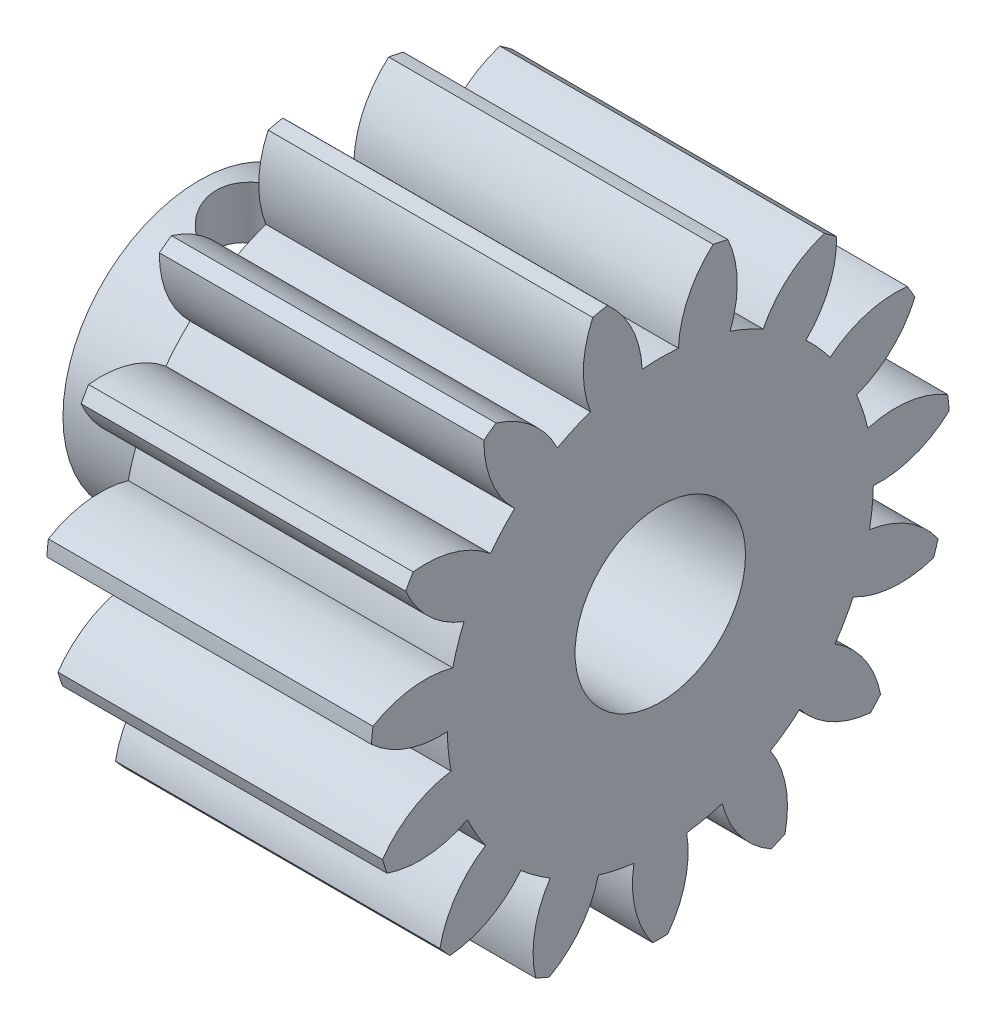
SolidWorks part; units mm, degrees
ref_plane "Plane1" through (0, 0, 0) normal (0, 0, 1) x (1, 0, 0)
ref_plane "Plane2" through (0, 0, 0) normal (0, 1, 0) x (1, 0, 0)
ref_plane "Plane3" through (0, 0, 0) normal (1, 0, 0) x (0, 0, -1)
sketch "HoldingSke" plane through (0, 0, 0) normal (0, 1, 0) x (1, 0, 0)
  line L0 (0, 0) -> (0.9659, -0.2588)
  line L1 (-15, 0) -> (100, 0) construction
  line L2 (0, 0) -> (-2.1039, 2.3779)
  line L3 (0, 0) -> (-11.863, 4.5341)
  line L4 (0, 0) -> (8.3417, 2.2352)
  line L5 (0, 0) -> (-46.8476, -17.4728)
  line L6 (0, 0) -> (-10.5278, -7.1032)
  line L7 (-2.1039, 2.3779) -> (8.6586, 51.2059)
  line L8 (-76.2, 54.61) -> (-76.1, 54.61)
  line L9 (-71.009, 38.7566) -> (-53.1078, 45.2721)
  line L10 (-76.2, 71.12) -> (104.1128, 71.12)
  line L11 (0, 0) -> (-12.7, 0)
  line L12 (-76.2, 101.6) -> (-76.162, 101.6)
  line L13 (24.9733, 27.94) -> (52.9518, 28.4284)
  line L14 (24.9733, 27.94) -> (24.9743, 27.94)
  line L15 (24.9733, 27.94) -> (100.4006, 29.5858)
  line L16 (-63.627, -1) -> (-12.827, -1)
  circle A0 centre (0, 0) radius 0.4
  circle A1 centre (0, 0) radius 6.249
  circle A2 centre (0, 0) radius 37.5
  circle A3 centre (0, 0) radius 0.4
  dimension "MHD" = 12.498
  dimension "Hub_dia" = 75
  dimension "Bore" = 0.8
  dimension "MBD" = 0.8
  dimension "Num_teeth" = 15
  dimension "Pitch" = 1
  dimension "Overall_len" = 50
  dimension "Show_teeth" = 15
  dimension "Thickness" = 12.7
  dimension "OAL" = 50.0001
  dimension "T_dim" = 0.1
  dimension "Ap" = 20
  dimension "H" = 19.05
  dimension "Pitch_radius" = 180.3128
  dimension "Width" = 12.7
  dimension "Backlash" = 0.038
  dimension "Addendum_fac" = 1
  dimension "Dedendum_fac" = 1.25
  dimension "Clearance_fac" = 0.25
  dimension "Dedendum_add" = 0.001
  dimension "Module" = 1
sketch "BasProSke" plane through (0, 0, 0) normal (0, 1, 0) x (1, 0, 0)
  line L0 (-10, 0) -> (60, 0) construction
  line L1 (0, 0) -> (0, 8.5)
  line L2 (0, 0) -> (12.7, 0)
  line L3 (12.7, 0) -> (12.7, 8.5)
  line L4 (12.7, 8.5) -> (0, 8.5)
  dimension "Thickness" = 12.7
  dimension "Diameter" = 17
revolve "Base-Revolve" add sketch "BasProSke" angle 360 about L0
sketch "TooCutSke" plane through (0, 0, 0) normal (1, 0, 0) x (0, 0, -1)
  line L1 (0, 0) -> (0, 107) construction
  line L2 (0, 0) -> (-0.8504, 7.4516) construction
  line L3 (0, 0) -> (-3.1044, 14.6049) construction
  line L4 (-0.8504, 7.4516) -> (-1.5522, 7.3025) construction
  arc A0 (0.5316, 6.2263) -> (-0.5316, 6.2263) centre (0, 0) ccw
  arc A1 (1.5766, 8.3784) -> (-1.5766, 8.3784) centre (0, 0) ccw
  circle A2 centre (0, 0) radius 7.5 construction
  circle A3 centre (0, 0) radius 7.0477 construction
  arc A4 (-0.5316, 6.2263) -> (-1.5766, 8.3784) centre (-3.5289, 6.1005) ccw
  arc A5 (1.5766, 8.3784) -> (0.5316, 6.2263) centre (3.5289, 6.1005) ccw
  dimension "Root_dia" = 12.498
  dimension "Overcut_dia" = 17.0508
  dimension "Pitch_dia" = 15
  dimension "Base_dia" = 14.0954
  dimension "Flank_rad" = 3
  dimension "Half_ang" = 12
  dimension "Half_CT" = 0.7175
extrude "ToothCut" cut sketch "TooCutSke" along normal through all
fillet "Breaks" [suppressed] radius 0.02
fillet "RootFillets" [suppressed] radius 0.251
pattern_circular "TeethCuts" count 15 every 24 about axis through (-10, 0, 0) along (1, 0, 0) of "ToothCut", "RootFillets", "Breaks"
sketch "HubNeaOneSke" plane through (0, 0, 0) normal (-1, 0, 0) x (0, 0, 1)
  circle A0 centre (0, 0) radius 6.249
  dimension "Diameter" = 12.498
extrude "HubNearOne" [suppressed] add sketch "HubNeaOneSke" along normal blind 37.3001
sketch "HubNeaBotSke" plane through (0, 0, 0) normal (-1, 0, 0) x (0, 0, 1)
  circle A0 centre (0, 0) radius 6.249
  dimension "Diameter" = 12.498
extrude "HubNearBoth" [suppressed] add sketch "HubNeaBotSke" along normal blind 18.65
ref_plane "FarPln" through (12.7, 0, 0) normal (1, 0, 0) x (0, 0, -1)
sketch "HubFarSke" plane through (12.7, 0, 0) normal (1, 0, 0) x (0, 0, -1)
  circle A0 centre (0, 0) radius 6.249
  dimension "Diameter" = 12.498
extrude "HubFar" [suppressed] add sketch "HubFarSke" along normal blind 18.65
sketch "BorSke" plane through (0, 0, 0) normal (1, 0, 0) x (0, 0, -1)
  circle A0 centre (0, 0) radius 0.4
  dimension "Diameter" = 0.8
extrude "Bore" cut sketch "BorSke" along normal mid plane 100.0001
sketch "KeySke" plane through (0, 0, 0) normal (1, 0, 0) x (0, 0, -1)
  line L0 (-0.05, 0) -> (-0.05, 0.5)
  line L1 (-0.05, 0.5) -> (0.05, 0.5)
  line L2 (0.05, 0.5) -> (0.05, 0)
  line L3 (0, 0) -> (0, 34) construction
  line L4 (-0.05, 0) -> (0.05, 0)
  dimension "Offset" = 0.5
  dimension "Width" = 0.1
extrude "Keyway" [suppressed] cut sketch "KeySke" along normal mid plane 100.0001
pattern_circular "Keyway2" [suppressed] count 2 every 90 about axis through (-10, 0, 0) along (1, 0, 0)
sketch "Croquis2" plane through (12.7, 0, 0) normal (1, 0, 0) x (0, 0, -1)
  arc A60 (-8.4736, 0.67) -> (-6.2478, -0.1222) centre (-6.436, 2.8719) ccw
  arc A61 (-6.2478, -0.1222) -> (-6.1367, -1.1795) centre (0, 0) ccw
  arc A62 (-6.1367, -1.1795) -> (-8.1491, -2.4171) centre (-5.6982, -4.1473) ccw
  arc A63 (-8.1491, -2.4171) -> (-8.0135, -2.8344) centre (0, 0) ccw
  arc A64 (-8.0135, -2.8344) -> (-5.658, -2.6528) centre (-7.0477, 0.0059) ccw
  arc A65 (-5.658, -2.6528) -> (-5.1264, -3.5735) centre (0, 0) ccw
  arc A66 (-5.1264, -3.5735) -> (-6.4614, -5.5227) centre (-3.5188, -6.1064) ccw
  arc A67 (-6.4614, -5.5227) -> (-6.1678, -5.8487) centre (0, 0) ccw
  arc A68 (-6.1678, -5.8487) -> (-4.0898, -4.7248) centre (-6.4408, -2.8612) ccw
  arc A69 (-4.0898, -4.7248) -> (-3.2297, -5.3497) centre (0, 0) ccw
  arc A70 (-3.2297, -5.3497) -> (-3.6565, -7.6733) centre (-0.7308, -7.0097) ccw
  arc A71 (-3.6565, -7.6733) -> (-3.2557, -7.8518) centre (0, 0) ccw
  arc A72 (-3.2557, -7.8518) -> (-1.8145, -5.9798) centre (-4.7202, -5.2335) ccw
  arc A73 (-1.8145, -5.9798) -> (-0.7746, -6.2008) centre (0, 0) ccw
  arc A74 (-0.7746, -6.2008) -> (-0.2194, -8.4972) centre (2.1834, -6.7009) ccw
  arc A75 (-0.2194, -8.4972) -> (0.2194, -8.4972) centre (0, 0) ccw
  arc A76 (0.2194, -8.4972) -> (0.7746, -6.2008) centre (-2.1834, -6.7009) ccw
  arc A77 (0.7746, -6.2008) -> (1.8145, -5.9798) centre (0, 0) ccw
  arc A78 (1.8145, -5.9798) -> (3.2557, -7.8518) centre (4.7202, -5.2335) ccw
  arc A79 (3.2557, -7.8518) -> (3.6565, -7.6733) centre (0, 0) ccw
  arc A80 (3.6565, -7.6733) -> (3.2297, -5.3497) centre (0.7308, -7.0097) ccw
  arc A81 (3.2297, -5.3497) -> (4.0898, -4.7248) centre (0, 0) ccw
  arc A82 (4.0898, -4.7248) -> (6.1678, -5.8487) centre (6.4408, -2.8612) ccw
  arc A83 (6.1678, -5.8487) -> (6.4614, -5.5227) centre (0, 0) ccw
  arc A84 (6.4614, -5.5227) -> (5.1264, -3.5735) centre (3.5188, -6.1064) ccw
  arc A85 (5.1264, -3.5735) -> (5.658, -2.6528) centre (0, 0) ccw
  arc A86 (5.658, -2.6528) -> (8.0135, -2.8344) centre (7.0477, 0.0059) ccw
  arc A87 (8.0135, -2.8344) -> (8.1491, -2.4171) centre (0, 0) ccw
  arc A88 (8.1491, -2.4171) -> (6.1367, -1.1795) centre (5.6982, -4.1473) ccw
  arc A89 (6.1367, -1.1795) -> (6.2478, -0.1222) centre (0, 0) ccw
  arc A90 (6.2478, -0.1222) -> (8.4736, 0.67) centre (6.436, 2.8719) ccw
  arc A91 (8.4736, 0.67) -> (8.4277, 1.1064) centre (0, 0) ccw
  arc A92 (8.4277, 1.1064) -> (6.0859, 1.4185) centre (6.8925, -1.471) ccw
  arc A93 (6.0859, 1.4185) -> (5.7573, 2.4296) centre (0, 0) ccw
  arc A94 (5.7573, 2.4296) -> (7.4685, 4.0586) centre (4.7115, 5.2414) ccw
  arc A95 (7.4685, 4.0586) -> (7.2491, 4.4386) centre (0, 0) ccw
  arc A96 (7.2491, 4.4386) -> (4.9828, 3.7712) centre (6.8949, 1.4595) ccw
  arc A97 (4.9828, 3.7712) -> (4.2714, 4.5613) centre (0, 0) ccw
  arc A98 (4.2714, 4.5613) -> (5.172, 6.7454) centre (2.1723, 6.7046) ccw
  arc A99 (5.172, 6.7454) -> (4.817, 7.0033) centre (0, 0) ccw
  arc A100 (4.817, 7.0033) -> (3.0181, 5.4718) centre (5.7052, 4.1378) ccw
  arc A101 (3.0181, 5.4718) -> (2.0469, 5.9043) centre (0, 0) ccw
  arc A102 (2.0469, 5.9043) -> (1.9812, 8.2659) centre (-0.7425, 7.0085) ccw
  arc A103 (1.9812, 8.2659) -> (1.5521, 8.3571) centre (0, 0) ccw
  arc A104 (1.5521, 8.3571) -> (0.5316, 6.2263) centre (3.5289, 6.1005) ccw
  arc A105 (0.5316, 6.2263) -> (-0.5316, 6.2263) centre (0, 0) ccw
  arc A106 (-0.5316, 6.2263) -> (-1.5521, 8.3571) centre (-3.5289, 6.1005) ccw
  arc A107 (-1.5521, 8.3571) -> (-1.9812, 8.2659) centre (0, 0) ccw
  arc A108 (-1.9812, 8.2659) -> (-2.0469, 5.9043) centre (0.7425, 7.0085) ccw
  arc A109 (-2.0469, 5.9043) -> (-3.0181, 5.4718) centre (0, 0) ccw
  arc A110 (-3.0181, 5.4718) -> (-4.817, 7.0033) centre (-5.7052, 4.1378) ccw
  arc A111 (-4.817, 7.0033) -> (-5.172, 6.7454) centre (0, 0) ccw
  arc A112 (-5.172, 6.7454) -> (-4.2714, 4.5613) centre (-2.1723, 6.7046) ccw
  arc A113 (-4.2714, 4.5613) -> (-4.9828, 3.7712) centre (0, 0) ccw
  arc A114 (-4.9828, 3.7712) -> (-7.2491, 4.4386) centre (-6.8949, 1.4595) ccw
  arc A115 (-7.2491, 4.4386) -> (-7.4685, 4.0586) centre (0, 0) ccw
  arc A116 (-7.4685, 4.0586) -> (-5.7573, 2.4296) centre (-4.7115, 5.2414) ccw
  arc A117 (-5.7573, 2.4296) -> (-6.0859, 1.4185) centre (0, 0) ccw
  arc A118 (-6.0859, 1.4185) -> (-8.4277, 1.1064) centre (-6.8925, -1.471) ccw
  arc A119 (-8.4277, 1.1064) -> (-8.4736, 0.67) centre (0, 0) ccw
  arc A120 (-8.4736, 0.67) -> (-6.2478, -0.1222) centre (-6.436, 2.8719) ccw
  arc A121 (-6.2478, -0.1222) -> (-6.1367, -1.1795) centre (0, 0) ccw
  arc A122 (-6.1367, -1.1795) -> (-8.1491, -2.4171) centre (-5.6982, -4.1473) ccw
  arc A123 (-8.1491, -2.4171) -> (-8.0135, -2.8344) centre (0, 0) ccw
  arc A124 (-8.0135, -2.8344) -> (-5.658, -2.6528) centre (-7.0477, 0.0059) ccw
  arc A125 (-5.658, -2.6528) -> (-5.1264, -3.5735) centre (0, 0) ccw
  arc A126 (-5.1264, -3.5735) -> (-6.4614, -5.5227) centre (-3.5188, -6.1064) ccw
  arc A127 (-6.4614, -5.5227) -> (-6.1678, -5.8487) centre (0, 0) ccw
  arc A128 (-6.1678, -5.8487) -> (-4.0898, -4.7248) centre (-6.4408, -2.8612) ccw
  arc A129 (-4.0898, -4.7248) -> (-3.2297, -5.3497) centre (0, 0) ccw
  arc A130 (-3.2297, -5.3497) -> (-3.6565, -7.6733) centre (-0.7308, -7.0097) ccw
  arc A131 (-3.6565, -7.6733) -> (-3.2557, -7.8518) centre (0, 0) ccw
  arc A132 (-3.2557, -7.8518) -> (-1.8145, -5.9798) centre (-4.7202, -5.2335) ccw
  arc A133 (-1.8145, -5.9798) -> (-0.7746, -6.2008) centre (0, 0) ccw
  arc A134 (-0.7746, -6.2008) -> (-0.2194, -8.4972) centre (2.1834, -6.7009) ccw
  arc A135 (-0.2194, -8.4972) -> (0.2194, -8.4972) centre (0, 0) ccw
  arc A136 (0.2194, -8.4972) -> (0.7746, -6.2008) centre (-2.1834, -6.7009) ccw
  arc A137 (0.7746, -6.2008) -> (1.8145, -5.9798) centre (0, 0) ccw
  arc A138 (1.8145, -5.9798) -> (3.2557, -7.8518) centre (4.7202, -5.2335) ccw
  arc A139 (3.2557, -7.8518) -> (3.6565, -7.6733) centre (0, 0) ccw
  arc A140 (3.6565, -7.6733) -> (3.2297, -5.3497) centre (0.7308, -7.0097) ccw
  arc A141 (3.2297, -5.3497) -> (4.0898, -4.7248) centre (0, 0) ccw
  arc A142 (4.0898, -4.7248) -> (6.1678, -5.8487) centre (6.4408, -2.8612) ccw
  arc A143 (6.1678, -5.8487) -> (6.4614, -5.5227) centre (0, 0) ccw
  arc A144 (6.4614, -5.5227) -> (5.1264, -3.5735) centre (3.5188, -6.1064) ccw
  arc A145 (5.1264, -3.5735) -> (5.658, -2.6528) centre (0, 0) ccw
  arc A146 (5.658, -2.6528) -> (8.0135, -2.8344) centre (7.0477, 0.0059) ccw
  arc A147 (8.0135, -2.8344) -> (8.1491, -2.4171) centre (0, 0) ccw
  arc A148 (8.1491, -2.4171) -> (6.1367, -1.1795) centre (5.6982, -4.1473) ccw
  arc A149 (6.1367, -1.1795) -> (6.2478, -0.1222) centre (0, 0) ccw
  arc A150 (6.2478, -0.1222) -> (8.4736, 0.67) centre (6.436, 2.8719) ccw
  arc A151 (8.4736, 0.67) -> (8.4277, 1.1064) centre (0, 0) ccw
  arc A152 (8.4277, 1.1064) -> (6.0859, 1.4185) centre (6.8925, -1.471) ccw
  arc A153 (6.0859, 1.4185) -> (5.7573, 2.4296) centre (0, 0) ccw
  arc A154 (5.7573, 2.4296) -> (7.4685, 4.0586) centre (4.7115, 5.2414) ccw
  arc A155 (7.4685, 4.0586) -> (7.2491, 4.4386) centre (0, 0) ccw
  arc A156 (7.2491, 4.4386) -> (4.9828, 3.7712) centre (6.8949, 1.4595) ccw
  arc A157 (4.9828, 3.7712) -> (4.2714, 4.5613) centre (0, 0) ccw
  arc A158 (4.2714, 4.5613) -> (5.172, 6.7454) centre (2.1723, 6.7046) ccw
  arc A159 (5.172, 6.7454) -> (4.817, 7.0033) centre (0, 0) ccw
  arc A160 (4.817, 7.0033) -> (3.0181, 5.4718) centre (5.7052, 4.1378) ccw
  arc A161 (3.0181, 5.4718) -> (2.0469, 5.9043) centre (0, 0) ccw
  arc A162 (2.0469, 5.9043) -> (1.9812, 8.2659) centre (-0.7425, 7.0085) ccw
  arc A163 (1.9812, 8.2659) -> (1.5521, 8.3571) centre (0, 0) ccw
  arc A164 (1.5521, 8.3571) -> (0.5316, 6.2263) centre (3.5289, 6.1005) ccw
  arc A165 (0.5316, 6.2263) -> (-0.5316, 6.2263) centre (0, 0) ccw
  arc A166 (-0.5316, 6.2263) -> (-1.5521, 8.3571) centre (-3.5289, 6.1005) ccw
  arc A167 (-1.5521, 8.3571) -> (-1.9812, 8.2659) centre (0, 0) ccw
  arc A168 (-1.9812, 8.2659) -> (-2.0469, 5.9043) centre (0.7425, 7.0085) ccw
  arc A169 (-2.0469, 5.9043) -> (-3.0181, 5.4718) centre (0, 0) ccw
  arc A170 (-3.0181, 5.4718) -> (-4.817, 7.0033) centre (-5.7052, 4.1378) ccw
  arc A171 (-4.817, 7.0033) -> (-5.172, 6.7454) centre (0, 0) ccw
  arc A172 (-5.172, 6.7454) -> (-4.2714, 4.5613) centre (-2.1723, 6.7046) ccw
  arc A173 (-4.2714, 4.5613) -> (-4.9828, 3.7712) centre (0, 0) ccw
  arc A174 (-4.9828, 3.7712) -> (-7.2491, 4.4386) centre (-6.8949, 1.4595) ccw
  arc A175 (-7.2491, 4.4386) -> (-7.4685, 4.0586) centre (0, 0) ccw
  arc A176 (-7.4685, 4.0586) -> (-5.7573, 2.4296) centre (-4.7115, 5.2414) ccw
  arc A177 (-5.7573, 2.4296) -> (-6.0859, 1.4185) centre (0, 0) ccw
  arc A178 (-6.0859, 1.4185) -> (-8.4277, 1.1064) centre (-6.8925, -1.471) ccw
  arc A179 (-8.4277, 1.1064) -> (-8.4736, 0.67) centre (0, 0) ccw
  dimension "D1" = 0
extrude "Cortar-Extruir1" cut sketch "Croquis2" against normal blind 3.18
ref_plane "Plano2" through (4.76, 0, 0) normal (1, 0, 0) x (0, 0, -1)
sketch "Croquis3" plane through (4.76, 0, 0) normal (1, 0, 0) x (0, 0, -1)
  circle A0 centre (0, 0) radius 7.5
  dimension "D1" = 15
sketch "Croquis4" plane through (9.52, 0, 0) normal (1, 0, 0) x (0, 0, -1)
  circle A0 centre (0, 0) radius 2.5
  dimension "D1" = 5
extrude "Cortar-Extruir2" cut sketch "Croquis4" against normal up to surface (9.52 mm away) up to face at (0, 0, -0.4)
sketch "Croquis5" plane through (0, 0, 0) normal (-1, 0, 0) x (0, 0, 1)
  circle A0 centre (0, 0) radius 4
  circle A1 centre (0, 0) radius 2.5 construction
  circle A2 centre (0, 0) radius 2.5
  dimension "D1" = 8
extrude "Saliente-Extruir1" add sketch "Croquis5" along normal blind 4
sketch "Croquis6" plane through (0, 0, 0) normal (0, 1, 0) x (1, 0, 0)
  line L0 (-4, -4) -> (0, -4) construction
  line L1 (0, 0.5316) -> (0, -0.5316) construction
  circle A0 centre (-2, 0) radius 1.5
  dimension "D1" = 3
  dimension "D2" = 4
  dimension "D3" = 2
extrude "Cortar-Extruir3" cut sketch "Croquis6" against normal through all both and the other way through all
fillet "Redondeo2" radius 0.25 1 edges at (0, 0, -4)
equation "' \"Module@HoldingSke\" = 6.35"
equation "' \"Num_teeth@HoldingSke\" = 12"
equation "' \"Ap@HoldingSke\" =  20"
equation "' \"Ap@HoldingSke\" = 20"
equation "' \"Width@HoldingSke\" = 0.5 * 25.4"
equation "' \"Hub_dia@HoldingSke\"= 1 * 25.4"
equation "' \"Hub_dia@HoldingSke\" = 1 * 25.4"
equation "' \"Overall_len@HoldingSke\" = 1.0 * 25.4"
equation "' \"Bore@HoldingSke\" = 0.75 * 25.4"
equation "' \"T_dim@HoldingSke\" = 0.1 * 25.4"
equation "' \"Width@KeySke\" = 0.25 * 25.4"
equation "' \"Show_teeth@HoldingSke\" = 13"
equation "' \"Backlash@HoldingSke\" = 0.009 * 25.4"
equation "' \"Addendum_fac@HoldingSke\" = 1.0"
equation "' \"Dedendum_fac@HoldingSke\" = 1.25"
equation "' \"Dedendum_add@HoldingSke\" = 0.00005 * 25.4"
equation "' \"Clearance_fac@HoldingSke\" = 0.25"
equation "\"Pitch@HoldingSke\" = 1 / \"Module@HoldingSke\""
equation "\"Overcut_dia@TooCutSke\" = (\"Num_teeth@HoldingSke\" + 2 * \"Addendum_fac@HoldingSke\") / \"Pitch@HoldingSke\" + 0.002 * 25.4"
equation "\"Pitch_dia@TooCutSke\" = \"Num_teeth@HoldingSke\" / \"Pitch@HoldingSke\""
equation "\"Base_dia@TooCutSke\" = \"Num_teeth@HoldingSke\" / \"Pitch@HoldingSke\" * cos((\"Ap@HoldingSke\"  * 3.14159265 / 180))"
equation "\"Root_dia@TooCutSke\" = (\"Num_teeth@HoldingSke\" + 2) / \"Pitch@HoldingSke\" - 2 * (\"Addendum_fac@HoldingSke\" + \"Dedendum_fac@HoldingSke\") / \"Pitch@HoldingSke\" - \"Dedendum_add@HoldingSke\" * 2"
equation "\"Half_ang@TooCutSke\" = 180 / \"Num_teeth@HoldingSke\""
equation "\"Half_CT@TooCutSke\" = \"Num_teeth@HoldingSke\" / \"Pitch@HoldingSke\" * sin((3.14159265 / 2 / \"Num_teeth@HoldingSke\")) / 2 - 7 * \"Backlash@HoldingSke\" / 4"
equation "\"Flank_rad@TooCutSke\" = \"Num_teeth@HoldingSke\" / \"Pitch@HoldingSke\" / 5"
equation "\"Radius@RootFillets\" = \"Clearance_fac@HoldingSke\" / \"Pitch@HoldingSke\" + \"Dedendum_add@HoldingSke\""
equation "\"Break_rad@Breaks\" = 0.02 / \"Pitch@HoldingSke\""
equation "\"Thickness@HoldingSke\" = \"Width@HoldingSke\""
equation "\"OAL@HoldingSke\" = \"Thickness@HoldingSke\""
equation "\"MHD@HoldingSke\" = (\"Num_teeth@HoldingSke\" + 2) / \"Pitch@HoldingSke\" - 2 * (\"Addendum_fac@HoldingSke\" + \"Dedendum_fac@HoldingSke\")  / \"Pitch@HoldingSke\" - \"Dedendum_add@HoldingSke\" * 2"
equation "\"MBD@HoldingSke\" = (\"Num_teeth@HoldingSke\" + 2) / \"Pitch@HoldingSke\" - 2 * (\"Addendum_fac@HoldingSke\" + \"Dedendum_fac@HoldingSke\")  / \"Pitch@HoldingSke\" - \"Dedendum_add@HoldingSke\" * 2 - 0.002 * 25.4"
equation "\"MHD@HoldingSke\" = ((sgn( \"MHD@HoldingSke\" - \"Hub_dia@HoldingSke\" )-1)*( \"MHD@HoldingSke\" - \"Hub_dia@HoldingSke\" ))/-2+ \"Hub_dia@HoldingSke\""
equation "\"MBD@HoldingSke\" = ((sgn( \"MBD@HoldingSke\" - \"Bore@HoldingSke\" )-1)*( \"MBD@HoldingSke\" - \"Bore@HoldingSke\" ))/-2+ \"Bore@HoldingSke\""
equation "\"OAL@HoldingSke\" = ((sgn( \"OAL@HoldingSke\" - \"Overall_len@HoldingSke\" )+1)*( \"OAL@HoldingSke\" - \"Overall_len@HoldingSke\" ))/2 + \"Overall_len@HoldingSke\" + 0.000002 * 25.4"
equation "\"Num_teeth@TeethCuts\" = int( \"Show_teeth@HoldingSke\" ) + 1"
equation "\"Num_teeth@TeethCuts\" = ((sgn( \"Num_teeth@TeethCuts\" - \"Num_teeth@HoldingSke\" )-1)*( \"Num_teeth@TeethCuts\" - \"Num_teeth@HoldingSke\" ))/-2+ \"Num_teeth@HoldingSke\""
equation "\"Num_teeth@TeethCuts\" = ((sgn( \"Num_teeth@TeethCuts\" - 2.0)+1)*( \"Num_teeth@TeethCuts\" - 2.0))/2 +2.0"
equation "\"Angle@TeethCuts\" = 360.0 / \"Num_teeth@HoldingSke\""
equation "\"Diameter@BasProSke\" = (\"Num_teeth@HoldingSke\" + 2 * \"Addendum_fac@HoldingSke\") / \"Pitch@HoldingSke\""
equation "\"Thickness@BasProSke\"  = \"Thickness@HoldingSke\""
equation "' \"Fillet_rad@BasProSke\" =  \"Thickness@HoldingSke\" * 0.05"
equation "' \"Fillet_rad@BasProSke\" = \"Thickness@HoldingSke\" * 0.05"
equation "\"MHD@HoldingSke\" = ((sgn( \"MHD@HoldingSke\" - \"Root_dia@TooCutSke\" )-1)*( \"MHD@HoldingSke\" - \"Root_dia@TooCutSke\" ))/-2+ \"Root_dia@TooCutSke\""
equation "\"Diameter@HubNeaOneSke\" = \"MHD@HoldingSke\""
equation "\"Length@HubNearOne\" = \"OAL@HoldingSke\" - \"Thickness@BasProSke\""
equation "\"Diameter@HubNeaBotSke\" = \"MHD@HoldingSke\""
equation "\"Length@HubNearBoth\" = ( \"OAL@HoldingSke\" - \"Thickness@BasProSke\" ) / 2.0"
equation "\"Thickness@FarPln\" = \"Thickness@BasProSke\""
equation "\"Diameter@HubFarSke\" = \"MHD@HoldingSke\""
equation "\"Length@HubFar\" = ( \"OAL@HoldingSke\" - \"Thickness@BasProSke\" ) / 2.0"
equation "\"Diameter@BorSke\" = \"MBD@HoldingSke\""
equation "\"D1@Bore\" = \"OAL@HoldingSke\" * 2.0"
equation "\"D1@Keyway\" = \"OAL@HoldingSke\" * 2.0"
equation "\"Offset@KeySke\" = \"T_dim@HoldingSke\" + \"MBD@HoldingSke\" / 2.0"
